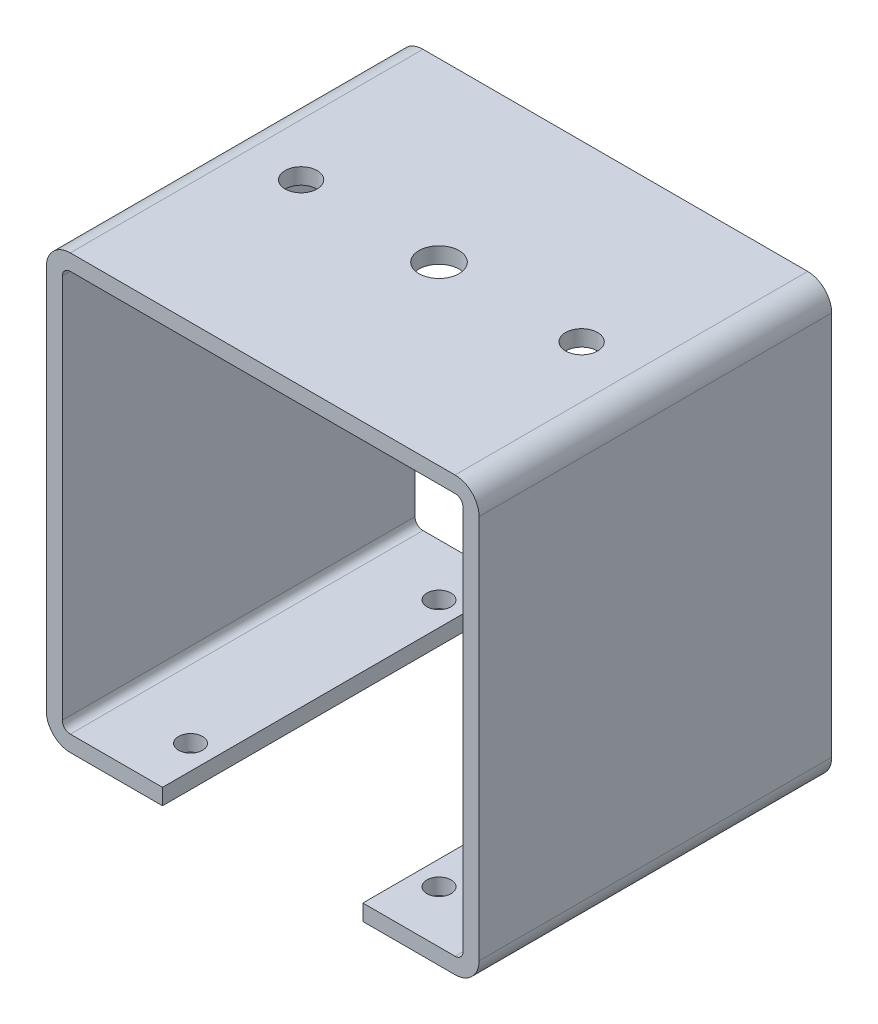
SolidWorks part; units mm, degrees
ref_plane "Front Plane" through (0, 0, 0) normal (0, 0, 1) x (1, 0, 0)
ref_plane "Top Plane" through (0, 0, 0) normal (0, 1, 0) x (1, 0, 0)
ref_plane "Right Plane" through (0, 0, 0) normal (1, 0, 0) x (0, 0, -1)
sketch "Sketch1" plane through (0, 0, 0) normal (0, 0, 1) x (1, 0, 0)
  line L0 (0, -651.9423) -> (0, 31945.1704) construction
  line L1 (-25, 50) -> (25, 50)
  line L2 (-25, 50) -> (-25, 0)
  line L3 (-25, 0) -> (-12.5, 0)
  line L4 (-12.5, 0) -> (-12.5, -2)
  line L5 (-12.5, -2) -> (-27, -2)
  line L6 (-27, -2) -> (-27, 52)
  line L7 (-27, 52) -> (27, 52)
  line L8 (27, 52) -> (27, -2)
  line L9 (27, -2) -> (12.5, -2)
  line L10 (12.5, -2) -> (12.5, 0)
  line L11 (12.5, 0) -> (25, 0)
  line L12 (25, 0) -> (25, 50)
  point P6 (0, 50)
  dimension "D1" = 50
  dimension "D2" = 25
  dimension "D3" = 2
  dimension "D4" = 2
  dimension "D5" = 2
  dimension "D6" = 2
  dimension "D7" = 2
extrude "Boss-Extrude1" add sketch "Sketch1" along normal blind 44
sketch "Sketch2" plane through (0, -2, 0) normal (0, -1, 0) x (-1, 0, 0)
  line L0 (-1012.5, -22) -> (48987.5, -22) construction
  line L1 (-12.5, -44) -> (-12.5, 0) construction
  line L2 (0, -1000) -> (0, 49000) construction
  line L3 (15.5, -37.5) -> (-15.5, -37.5) construction
  line L4 (15.5, -6.5) -> (-15.5, -6.5) construction
  line L5 (0, -37.5) -> (0, -6.5)
  circle A0 centre (15.5, -37.5) radius 1.5
  circle A1 centre (-15.5, -37.5) radius 1.5
  circle A2 centre (-15.5, -6.5) radius 1.5
  circle A3 centre (15.5, -6.5) radius 1.5
  point P5 (-12.5, -22)
  point P11 (0, -37.5)
  point P14 (0, -6.5)
  point P17 (0, -22)
  dimension "D4" = 3
  dimension "D1" = 31
  dimension "D2" = 31
  dimension "D3" = 31
extrude "Cut-Extrude1" cut sketch "Sketch2" against normal blind 32 contours A0 | A1 | A2 | A3
sketch "Sketch3" plane through (0, 50, 0) normal (0, -1, 0) x (1, 0, 0)
  line L0 (0, 44) -> (0, 0) construction
  line L1 (-25, 44) -> (25, 44) construction
  circle A0 centre (0, 22) radius 2.5
  dimension "D1" = 5
extrude "Cut-Extrude2" cut sketch "Sketch3" against normal through all
sketch "Sketch4" plane through (0, 52, 0) normal (0, 1, 0) x (1, 0, 0)
  line L0 (0, 0) -> (0, -44) construction
  line L1 (27, -44) -> (-27, -44) construction
  circle A0 centre (-17.5, -21.7049) radius 2
  circle A1 centre (17.5, -21.7049) radius 2
  point P0 (0, -22)
  point P7 (-17.5, -21.7049)
  dimension "D3" = 4
extrude "Cut-Extrude3" cut sketch "Sketch4" against normal blind 44
fillet "Fillet1" radius 1 4 edges at (-25, 50, 22) (25, 50, 22) (25, 0, 22) (-25, 0, 22)
fillet "Fillet2" radius 3 4 edges at (-27, 52, 22) (27, 52, 22) (27, -2, 22) (-27, -2, 22)
